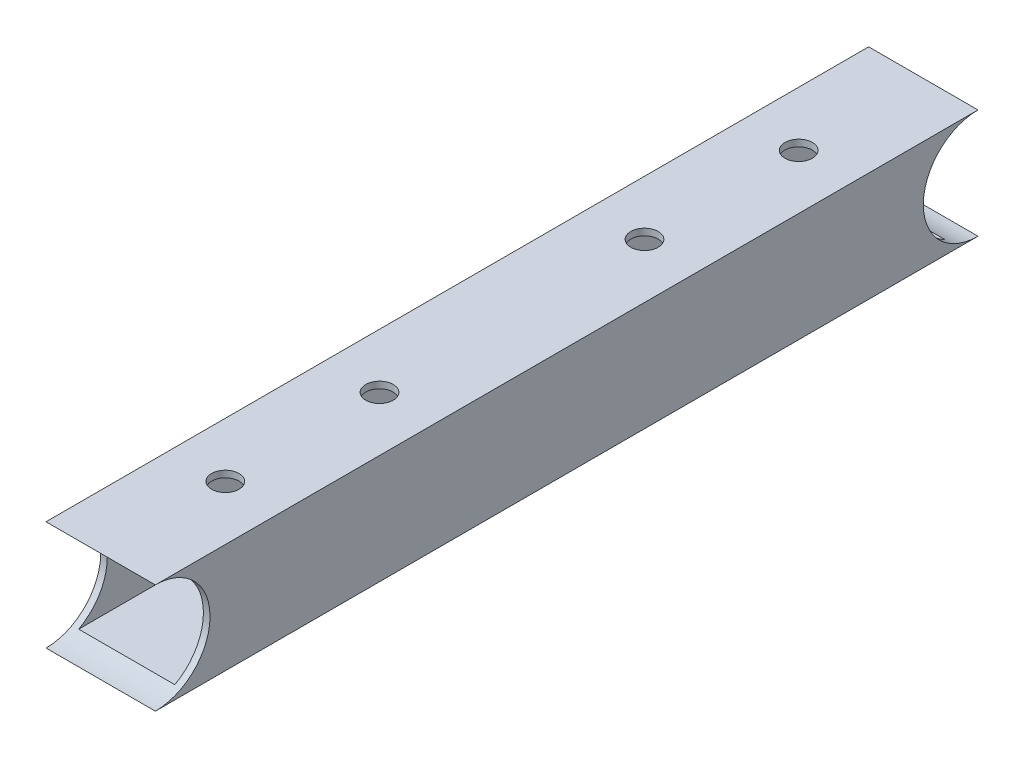
SolidWorks part; units mm, degrees
material "AISI 1020"
ref_plane "Front Plane" through (0, 0, 0) normal (0, 0, 1) x (1, 0, 0)
ref_plane "Top Plane" through (0, 0, 0) normal (0, 1, 0) x (1, 0, 0)
ref_plane "Right Plane" through (0, 0, 0) normal (1, 0, 0) x (0, 0, -1)
sketch "Sketch1" plane through (0, 0, 0) normal (0, 0, 1) x (1, 0, 0)
  line L1 (-17.526, 17.526) -> (17.526, 17.526)
  line L2 (-17.526, 17.526) -> (-17.526, -17.526)
  line L3 (-17.526, -17.526) -> (17.526, -17.526)
  line L4 (17.526, 17.526) -> (17.526, -17.526)
  line L5 (-17.526, 17.526) -> (17.526, -17.526) construction
  line L6 (-17.526, -17.526) -> (17.526, 17.526) construction
  line L7 (-19.939, 19.939) -> (19.939, 19.939)
  line L8 (-19.939, 19.939) -> (-19.939, -19.939)
  line L9 (-19.939, -19.939) -> (19.939, -19.939)
  line L10 (19.939, 19.939) -> (19.939, -19.939)
  line L11 (-19.939, 19.939) -> (19.939, -19.939) construction
  line L12 (-19.939, -19.939) -> (19.939, 19.939) construction
  point P0 (0, 0)
  point P6 (0, 0)
  dimension "D1" = 39.878
  dimension "D2" = 2.413
extrude "Boss-Extrude1" add sketch "Sketch1" along normal blind 300
sketch "Sketch2" plane through (19.939, 0, 0) normal (1, 0, 0) x (0, 0, -1)
  line L0 (-300, -19.939) -> (-300, 19.939) construction
  circle A0 centre (-300, 0) radius 19.939
  circle A1 centre (0, 0) radius 19.939
extrude "Cut-Extrude1" cut sketch "Sketch2" against normal blind 300
sketch "Sketch3" plane through (0, 19.939, 0) normal (0, 1, 0) x (1, 0, 0)
  line L0 (-19.939, -150) -> (19.939, -150) construction
  line L1 (-19.939, -300) -> (-19.939, 0) construction
  line L2 (19.939, -300) -> (19.939, 0) construction
  line L3 (0, -150) -> (0, -198.315) construction
  line L8 (0, -198.315) -> (0, -254.545) construction
  circle A8 centre (0, -198.315) radius 5
  circle A9 centre (0, -254.545) radius 5
  circle A10 centre (0, -101.685) radius 5
  circle A11 centre (0, -45.455) radius 5
  dimension "D3" = 10
  dimension "D1" = 48.315
  dimension "D2" = 56.23
extrude "Cut-Extrude2" cut sketch "Sketch3" against normal blind 95
